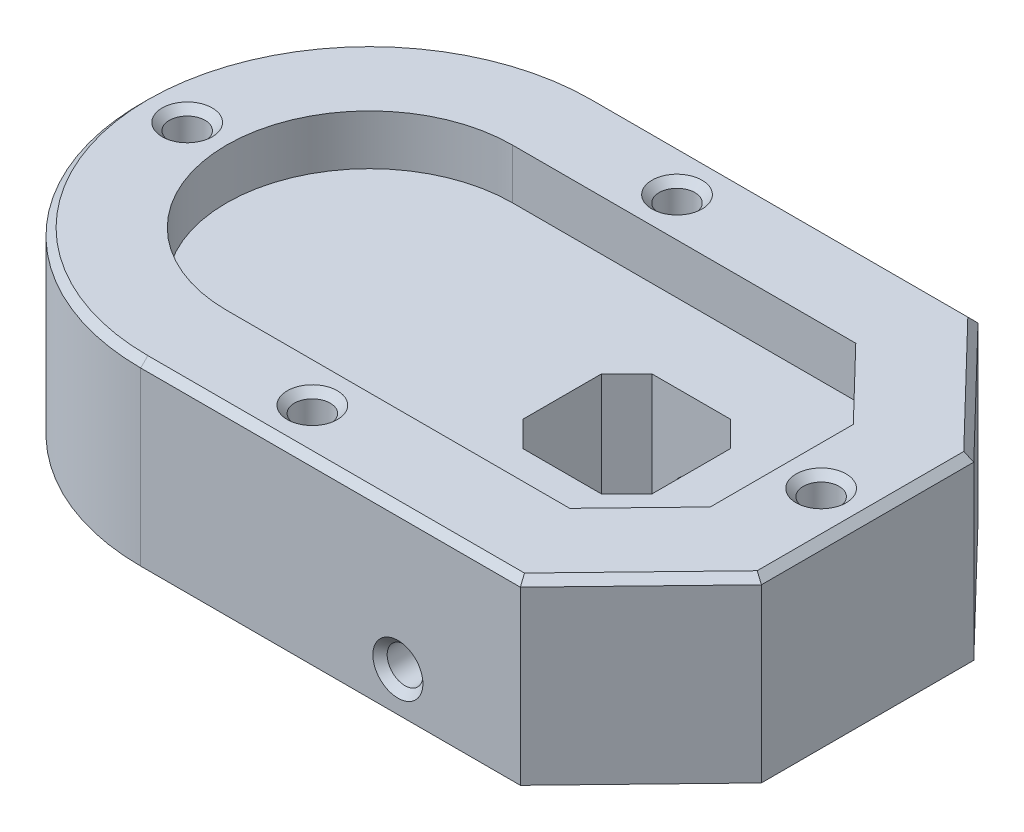
SolidWorks part; units mm, degrees
ref_plane "Front Plane" through (0, 0, 0) normal (0, 0, 1) x (1, 0, 0)
ref_plane "Top Plane" through (0, 0, 0) normal (0, 1, 0) x (1, 0, 0)
ref_plane "Right Plane" through (0, 0, 0) normal (1, 0, 0) x (0, 0, -1)
sketch "Sketch1" plane through (0, 0, 0) normal (0, 1, 0) x (1, 0, 0)
  line L0 (40.1569, 10) -> (40.1569, -10)
  line L1 (-37.5, 20) -> (30.5, 20)
  line L2 (-37.5, 20) -> (-37.5, -20)
  line L3 (-37.5, -20) -> (30.5, -20)
  line L4 (40.1569, 10) -> (40.1569, -10)
  line L5 (-37.5, 20) -> (37.5, -20) construction
  line L6 (-37.5, -20) -> (37.5, 20) construction
  line L7 (30.5, 20) -> (40.1569, 10)
  line L8 (40.1569, -10) -> (30.5, -20)
  arc A0 (-17.5, 20) -> (-17.5, -20) centre (-17.5, 0) ccw
  point P5 (40.1569, 0)
  point P6 (40.1569, 0)
  point P7 (0, 0)
  dimension "D1" = 40
  dimension "D2" = 75
  dimension "D3" = 20
  dimension "D4" = 46
  dimension "D5" = 46
  dimension "D6" = 40
  dimension "D7" = 68
extrude "Boss-Extrude1" add sketch "Sketch1" along normal blind 18 contours L1 A0 L3 L8 L0 L7
sketch "Sketch2" plane through (0, 0, 0) normal (0, -1, 0) x (1, 0, 0)
  line L0 (27.5, 5.5) -> (27.5, -5.5)
  line L1 (23.9645, 9.0355) -> (27.5, 5.5)
  line L2 (-17.5, 20) -> (30.5, 20) construction
  line L3 (23.9645, 9.0355) -> (12.9645, 9.0355)
  line L4 (12.9645, 9.0355) -> (9.4289, 5.5)
  line L5 (9.4289, 5.5) -> (9.4289, -5.5)
  line L6 (9.4289, -5.5) -> (12.9645, -9.0355)
  line L7 (12.9645, -9.0355) -> (23.9645, -9.0355)
  line L8 (27.5, -5.5) -> (23.9645, -9.0355)
  line L9 (30.5, 20) -> (30.5, -20) construction
  point P5 (27.5, 0)
  dimension "D1" = 11
  dimension "D2" = 45
  dimension "D3" = 45
  dimension "D4" = 5
  dimension "D5" = 3
extrude "Cut-Extrude1" cut sketch "Sketch2" against normal up to surface (18 mm away) up to face at (14.3856, 18, 0)
sketch "Sketch3" plane through (0, 0, 20) normal (0, 0, 1) x (1, 0, 0)
  line L0 (18.4645, 3) -> (18.4645, 0) construction
  line L1 (-17.5, 0) -> (30.5, 0) construction
  line L2 (23.9645, 0) -> (12.9645, 0) construction
  circle A0 centre (18.4645, 5.5) radius 2.5
  dimension "D2" = 5
  dimension "D1" = 3
sketch "Sketch4" plane through (0, 0, 0) normal (0, -1, 0) x (1, 0, 0)
  line L0 (30.5, 20) -> (-17.5, 20)
  line L1 (-17.5, 20) -> (30.5, 20) construction
  line L2 (-17.5, -20) -> (30.5, -20)
  line L3 (30.5, -20) -> (40.1569, -10)
  line L4 (40.1569, -10) -> (40.1569, 10)
  line L5 (30.5, 20) -> (40.1569, 10)
  line L6 (40.1569, 10) -> (30.5, 20) construction
  line L7 (40.1569, -10) -> (40.1569, 10) construction
  line L8 (30.5, -20) -> (40.1569, -10) construction
  line L9 (-17.5, -20) -> (30.5, -20) construction
  arc A0 (-17.5, 20) -> (-17.5, -20) centre (-17.5, 0) ccw
  arc A1 (-17.5, 20) -> (-17.5, -20) centre (-17.5, 0) ccw construction
extrude "Extrude-Thin1" add sketch "Sketch4" against normal blind 25 thin
extrude "Cut-Extrude2" cut sketch "Sketch3" against normal through all both and the other way through all contours A0
chamfer "Chamfer1" distance 1 angle 45 8 edges at (9.0468, 25, 32) (-49.5, 25, 0) (9.0468, 25, -32) (43.8753, 25, -23.4242) (52.1569, 25, 0) (43.8753, 25, 23.4242) (20.9645, 5.5, 32) (20.9645, 5.5, -32)
sketch "Sketch6" plane through (0, 25, 0) normal (0, 1, 0) x (1, 0, 0)
  line L0 (51.1569, 0) -> (-48.5, 0) construction
  line L1 (51.1569, -14.4443) -> (51.1569, 14.4443) construction
  line L2 (0, 31) -> (0, 20) construction
  line L3 (0, -31) -> (0, -20) construction
  line L4 (51.1569, 0) -> (40.1569, 0) construction
  line L5 (-37.5, 0) -> (-48.5, 0) construction
  line L6 (35.1692, 31) -> (-17.5, 31) construction
  line L8 (-17.5, 20) -> (30.5, 20) construction
  line L9 (30.5, -20) -> (-17.5, -20) construction
  line L10 (-17.5, -31) -> (35.1692, -31) construction
  line L11 (40.1569, 10) -> (40.1569, -10) construction
  circle A0 centre (0, 25.5) radius 2.5
  circle A1 centre (0, -25.5) radius 2.5
  circle A2 centre (45.6569, 0) radius 2.5
  circle A3 centre (-43, 0) radius 2.5
  arc A4 (-17.5, 31) -> (-17.5, -31) centre (-17.5, 0) ccw construction
  arc A5 (-17.5, 20) -> (-17.5, -20) centre (-17.5, 0) ccw construction
  point P9 (0, 0)
  point P15 (-48.5, 0)
  dimension "D1" = 5
extrude "Cut-Extrude3" cut sketch "Sketch6" against normal through all both and the other way through all
chamfer "Chamfer3" distance 1 angle 45 4 edges at (0, 25, 23) (-43, 25, -2.5) (0, 25, -28) (45.6569, 25, -2.5)
